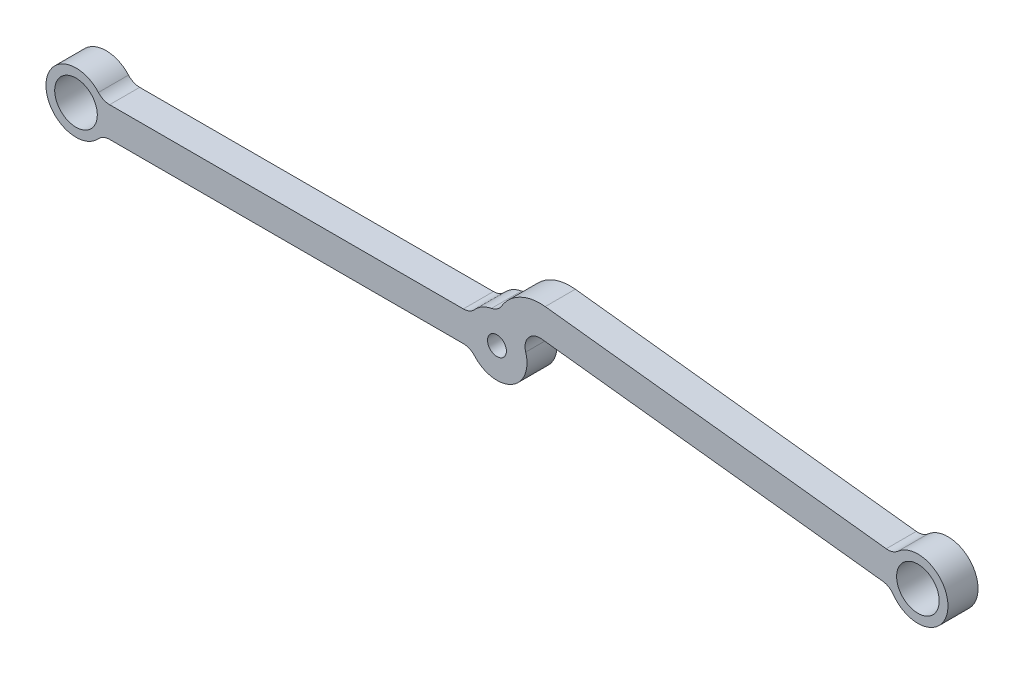
SolidWorks part; units mm, degrees
ref_plane "Front Plane" through (0, 0, 0) normal (0, 0, 1) x (1, 0, 0)
ref_plane "Top Plane" through (0, 0, 0) normal (0, 1, 0) x (1, 0, 0)
ref_plane "Right Plane" through (0, 0, 0) normal (1, 0, 0) x (0, 0, -1)
sketch "Sketch1" plane through (0, 0, 0) normal (0, 0, 1) x (1, 0, 0)
  line L0 (-85.725, 3.175) -> (-85.7116, 3.175)
  line L1 (-88.9, 6.35) -> (88.9, 6.35)
  line L2 (-88.9, 6.35) -> (-88.9, -6.35)
  line L3 (-88.9, -6.35) -> (88.9, -6.35)
  line L4 (88.9, 6.35) -> (88.9, -6.35)
  line L5 (-88.9, 6.35) -> (88.9, -6.35) construction
  line L6 (-88.9, -6.35) -> (88.9, 6.35) construction
  line L8 (-85.725, -3.175) -> (-5.4993, -3.175)
  line L10 (-83.4007, 3.175) -> (-5.4993, 3.175)
  line L11 (-85.725, 3.175) -> (85.725, 3.175) construction
  line L12 (-85.725, 3.175) -> (-85.725, -3.175) construction
  line L13 (-83.4007, -3.175) -> (-5.4993, -3.175)
  line L14 (-85.725, -3.175) -> (85.725, -3.175) construction
  line L15 (5.4993, 3.175) -> (83.4007, 3.175)
  line L16 (5.4993, -3.175) -> (83.4007, -3.175)
  line L17 (85.725, 3.175) -> (85.725, -3.175) construction
  line L18 (85.7116, 3.175) -> (85.725, 3.175)
  line L19 (85.7116, -3.175) -> (85.725, -3.175)
  line L20 (6.3084, -0.7257) -> (6.7438, 3.0593)
  line L21 (88.1743, -6.3084) -> (6.7438, 3.0593)
  line L22 (-6.3084, 0.7257) -> (-4.4215, 17.1275)
  line L23 (89.6257, 6.3084) -> (-4.4215, 17.1275)
  line L24 (88.9, 0) -> (-5.1473, 10.8191) construction
  line L25 (0, 0) -> (1.8869, 16.4018) construction
  line L26 (3.7827, 5.1004) -> (5.0411, 16.039)
  line L27 (-2.5257, 5.8261) -> (-1.2673, 16.7647)
  line L28 (3.1542, -0.3629) -> (5.0411, 16.039) construction
  line L29 (-3.1542, 0.3629) -> (-1.2673, 16.7647) construction
  line L30 (83.7996, 3.7827) -> (-4.7844, 13.9733)
  line L31 (83.0739, -2.5257) -> (-5.5101, 7.6649)
  line L32 (89.2629, 3.1542) -> (-4.7844, 13.9733) construction
  line L33 (88.5371, -3.1542) -> (-5.5101, 7.6649) construction
  circle A0 centre (-88.9, 0) radius 6.35
  circle A1 centre (88.9, 0) radius 6.35
  circle A2 centre (-88.9, 0) radius 4.4996
  circle A3 centre (88.9, 0) radius 4.4996
  circle A4 centre (0, 0) radius 1.9939
  circle A5 centre (0, 0) radius 6.35
  circle A6 centre (9.108, 2.7873) radius 3.175
  circle A7 centre (9.108, 2.7873) radius 9.525
  point P0 (0, 0)
  point P11 (-88.9, 0)
  point P13 (88.9, 0)
  dimension "D3" = 12.7
  dimension "D4" = 3.175
  dimension "D5" = 8.9992
  dimension "D6" = 3.81
  dimension "D7" = 3.175
  dimension "D1" = 3.9878
  dimension "D11" = 6.35
  dimension "D2" = 177.8
  dimension "D8" = 3.175
  dimension "D9" = 3.175
  dimension "D10" = 3.175
extrude "Boss-Extrude1" add sketch "Sketch1" along normal blind 6.35 contours A2 L2 A0 | A2 L2 A0 L8 | A2 L8 A0 L2 | A5 L22 L10 A0 L8 | A7 A5 A4 | A5 A7 A4 | A6 L31 L1 L26 A5 L15 | L1 A7 A5 L26 | L31 A7 L1 L26 | L1 L31 L26 | A6 L15 A5 | L31 A7 L1 | L26 A7 L31 | L1 A7 L26 L31 | A7 L1 L30 | A7 L31 L15 A1 L30 L1 | A1 L15 L31 | A3 L4 A1 | A3 L4 A1 | A5 L10 L22
fillet "Fillet2" radius 3.175 7 edges at (-5.4993, 3.175, 3.175) (83.7996, 3.7827, 3.175) (83.0739, -2.5257, 3.175) (-5.4993, -3.175, 3.175) (-83.4007, -3.175, 3.175) (-83.4007, 3.175, 3.175) (0.2721, 6.3442, 3.175)
